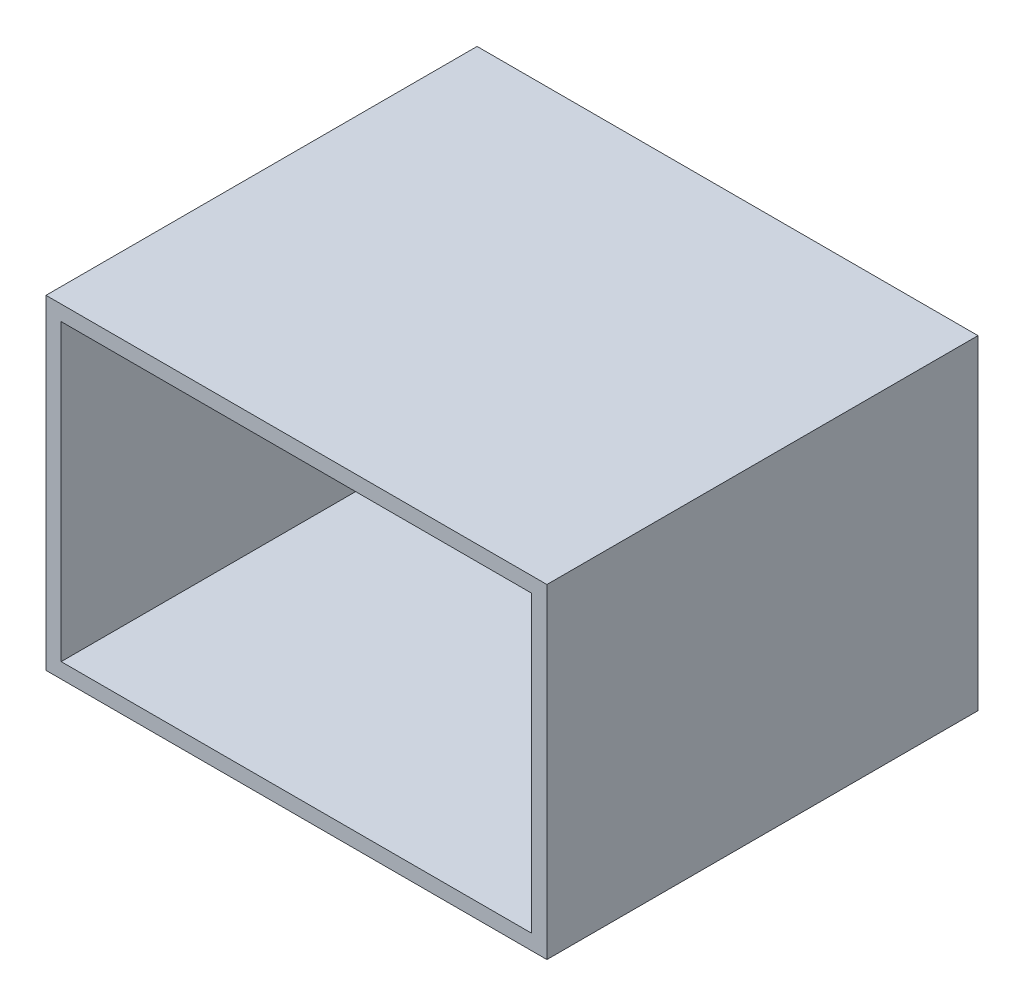
SolidWorks part; units mm, degrees
ref_plane "Front Plane" through (0, 0, 0) normal (0, 0, 1) x (1, 0, 0)
ref_plane "Top Plane" through (0, 0, 0) normal (0, 1, 0) x (1, 0, 0)
ref_plane "Right Plane" through (0, 0, 0) normal (1, 0, 0) x (0, 0, -1)
sketch "Sketch2" plane through (0, 0, 0) normal (0, 0, 1) x (1, 0, 0)
  line L0 (-82.5, 53.5) -> (82.5, 53.5)
  line L1 (-77.5, 48.5) -> (77.5, 48.5)
  line L2 (-77.5, 48.5) -> (-77.5, -48.5)
  line L3 (-77.5, -48.5) -> (77.5, -48.5)
  line L4 (77.5, 48.5) -> (77.5, -48.5)
  line L5 (0, -48.5) -> (0, 48.5) construction
  line L6 (-77.5, 0) -> (77.5, 0) construction
  line L7 (82.5, 53.5) -> (82.5, -53.5)
  line L8 (-82.5, -53.5) -> (82.5, -53.5)
  line L9 (-82.5, 53.5) -> (-82.5, -53.5)
  point P0 (0, 0)
  dimension "D1" = 155
  dimension "D2" = 97
  dimension "D3" = 5
extrude "Boss-Extrude1" add sketch "Sketch2" along normal blind 142
